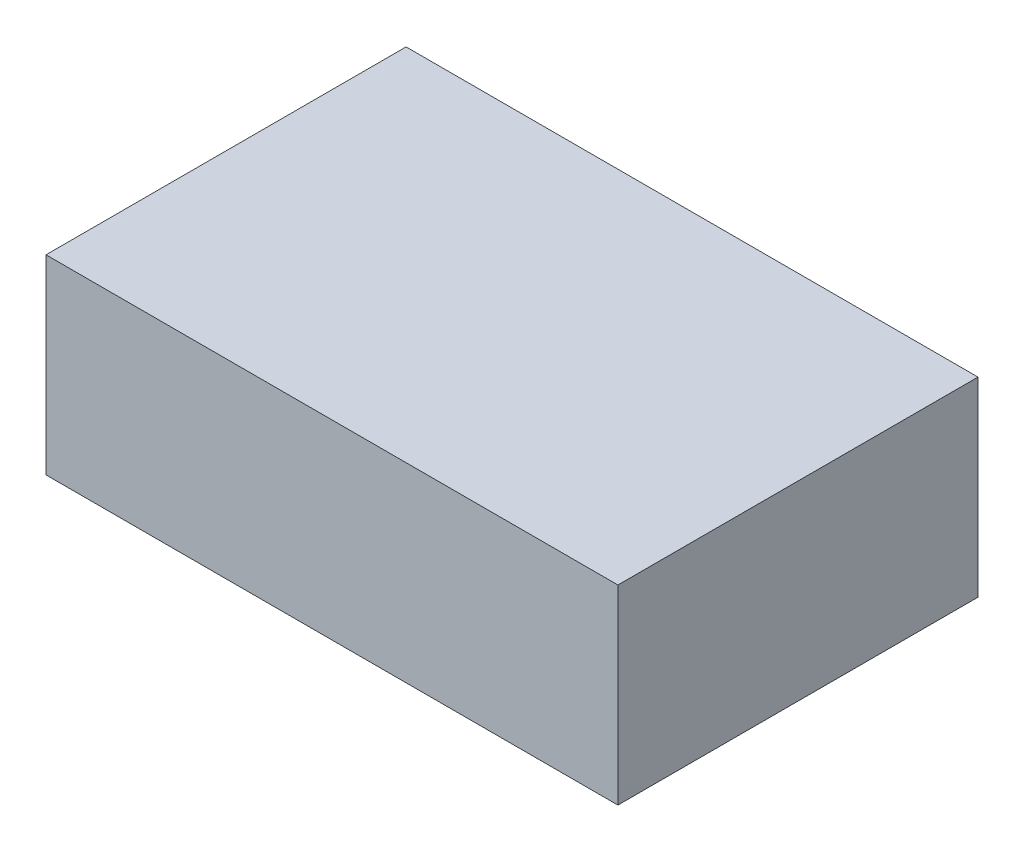
SolidWorks part; units mm, degrees
ref_plane "Alzado" through (0, 0, 0) normal (0, 0, 1) x (1, 0, 0)
ref_plane "Planta" through (0, 0, 0) normal (0, 1, 0) x (1, 0, 0)
ref_plane "Vista lateral" through (0, 0, 0) normal (1, 0, 0) x (0, 0, -1)
sketch "Croquis2" plane through (0, 0, 0) normal (0, 1, 0) x (1, 0, 0)
  line L1 (-67.5, 42.5) -> (67.5, 42.5)
  line L2 (-67.5, 42.5) -> (-67.5, -42.5)
  line L3 (-67.5, -42.5) -> (67.5, -42.5)
  line L4 (67.5, 42.5) -> (67.5, -42.5)
  line L5 (-67.5, 42.5) -> (67.5, -42.5) construction
  line L6 (-67.5, -42.5) -> (67.5, 42.5) construction
  point P0 (0, 0)
  dimension "D1" = 85
  dimension "D2" = 135
extrude "Saliente-Extruir2" add sketch "Croquis2" along normal blind 45
